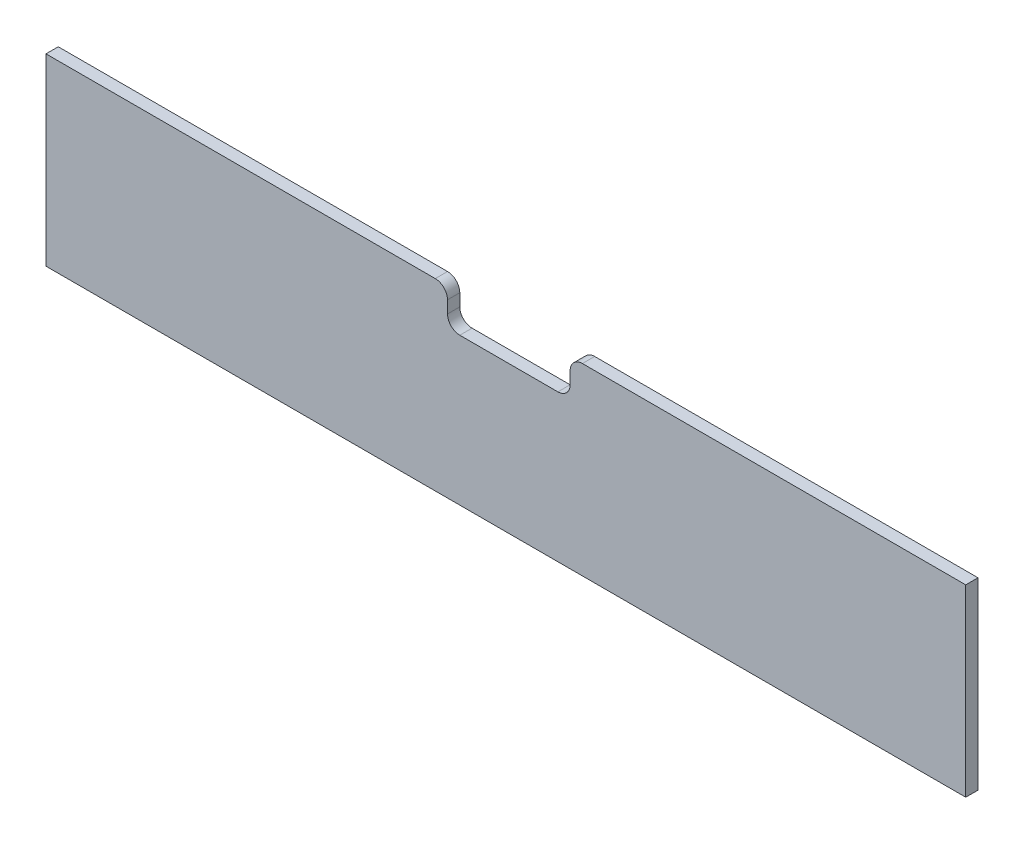
SolidWorks part; units mm, degrees
ref_plane "Front Plane" through (0, 0, 0) normal (0, 0, 1) x (1, 0, 0)
ref_plane "Top Plane" through (0, 0, 0) normal (0, 1, 0) x (1, 0, 0)
ref_plane "Right Plane" through (0, 0, 0) normal (1, 0, 0) x (0, 0, -1)
sketch "Sketch1" plane through (0, 0, 0) normal (0, 0, 1) x (1, 0, 0)
  line L1 (-476.25, -95.25) -> (476.25, -95.25)
  line L2 (-476.25, -95.25) -> (-476.25, 95.25)
  line L3 (-476.25, 95.25) -> (476.25, 95.25)
  line L4 (476.25, -95.25) -> (476.25, 95.25)
  line L5 (-476.25, -95.25) -> (476.25, 95.25) construction
  line L6 (-476.25, 95.25) -> (476.25, -95.25) construction
  point P0 (0, 0)
  dimension "D1" = 952.5
  dimension "D2" = 190.5
extrude "Boss-Extrude1" add sketch "Sketch1" along normal blind 12.7 contours L1 L4 L3 L2
sketch "Sketch5" plane through (0, 0, 12.7) normal (0, 0, 1) x (1, 0, 0)
  line L0 (-476.25, 95.25) -> (476.25, 95.25) construction
  line L1 (-60.4212, 57.15) -> (66.5788, 57.15)
  line L2 (-60.4212, 57.15) -> (-60.4212, 95.25)
  line L3 (-60.4212, 95.25) -> (66.5788, 95.25)
  line L4 (66.5788, 57.15) -> (66.5788, 95.25)
  line L5 (-60.4212, 57.15) -> (66.5788, 95.25) construction
  line L6 (-60.4212, 95.25) -> (66.5788, 57.15) construction
  point P0 (3.0788, 76.2)
  dimension "D1" = 38.1
  dimension "D2" = 127
extrude "Cut-Extrude3" cut sketch "Sketch5" against normal through all
fillet "Fillet1" radius 12.7 4 edges at (66.5788, 57.15, 6.35) (66.5788, 95.25, 6.35) (-60.4212, 57.15, 6.35) (-60.4212, 95.25, 6.35)
sketch "Sketch6" plane through (0, 0, 0) normal (0, 0, -1) x (-1, 0, 0)
  line L0 (0, 57.15) -> (0, -95.25) construction
  line L1 (47.7212, 57.15) -> (-53.8788, 57.15) construction
  line L2 (476.25, -95.25) -> (-476.25, -95.25) construction
  circle A0 centre (-425.45, 0) radius 3.175
  circle A1 centre (425.45, 0) radius 3.175
  dimension "D1" = 6.35
  dimension "D2" = 425.45
  dimension "D3" = 95.25
extrude "Cut-Extrude4" cut sketch "Sketch6" against normal blind 11.43
sketch "Sketch7" plane through (0, 0, 0) normal (0, 0, -1) x (-1, 0, 0)
  line L0 (-425.45, 0) -> (-425.45, 44.45) construction
  line L1 (-476.25, 0) -> (476.25, 0) construction
  line L2 (-476.25, -95.25) -> (-476.25, 95.25) construction
  line L3 (476.25, -95.25) -> (476.25, 95.25) construction
  line L4 (0, 57.15) -> (0, -95.25) construction
  line L5 (47.7212, 57.15) -> (-53.8788, 57.15) construction
  line L6 (476.25, -95.25) -> (-476.25, -95.25) construction
  circle A0 centre (-425.45, 44.45) radius 2.5
  circle A1 centre (-425.45, -44.45) radius 2.5
  circle A2 centre (425.45, -44.45) radius 2.5
  circle A3 centre (425.45, 44.45) radius 2.5
  dimension "D1" = 5
  dimension "D2" = 44.45
extrude "Cut-Extrude5" cut sketch "Sketch7" against normal blind 8
sketch "Sketch8" plane through (0, 0, 0) normal (0, 0, -1) x (-1, 0, 0)
  line L0 (-476.25, -82.55) -> (476.25, -82.55) construction
  line L1 (-476.25, -95.25) -> (-476.25, 95.25) construction
  line L2 (476.25, -95.25) -> (476.25, 95.25) construction
  line L3 (476.25, -95.25) -> (-476.25, -95.25) construction
  line L4 (-425.45, 0) -> (-425.45, -82.55) construction
  circle A0 centre (-425.45, -82.55) radius 2.5
  circle A5 centre (-212.725, -82.55) radius 2.5
  circle A6 centre (0, -82.55) radius 2.5
  circle A7 centre (212.725, -82.55) radius 2.5
  circle A8 centre (425.45, -82.55) radius 2.5
  dimension "D3" = 5
  dimension "D2" = 5
  dimension "D1" = 12.7
extrude "Cut-Extrude6" cut sketch "Sketch8" against normal blind 8
sketch "Sketch9" plane through (0, 0, 0) normal (0, 0, -1) x (-1, 0, 0)
  line L0 (-425.45, -82.55) -> (-212.725, -82.55) construction
  circle A0 centre (-319.0875, -82.55) radius 3.175
  circle A1 centre (-106.3625, -82.55) radius 3.175
  circle A2 centre (106.3625, -82.55) radius 3.175
  circle A3 centre (319.0875, -82.55) radius 3.175
  dimension "D1" = 6.35
  dimension "D2" = 4
extrude "Cut-Extrude7" cut sketch "Sketch9" against normal blind 11.43
